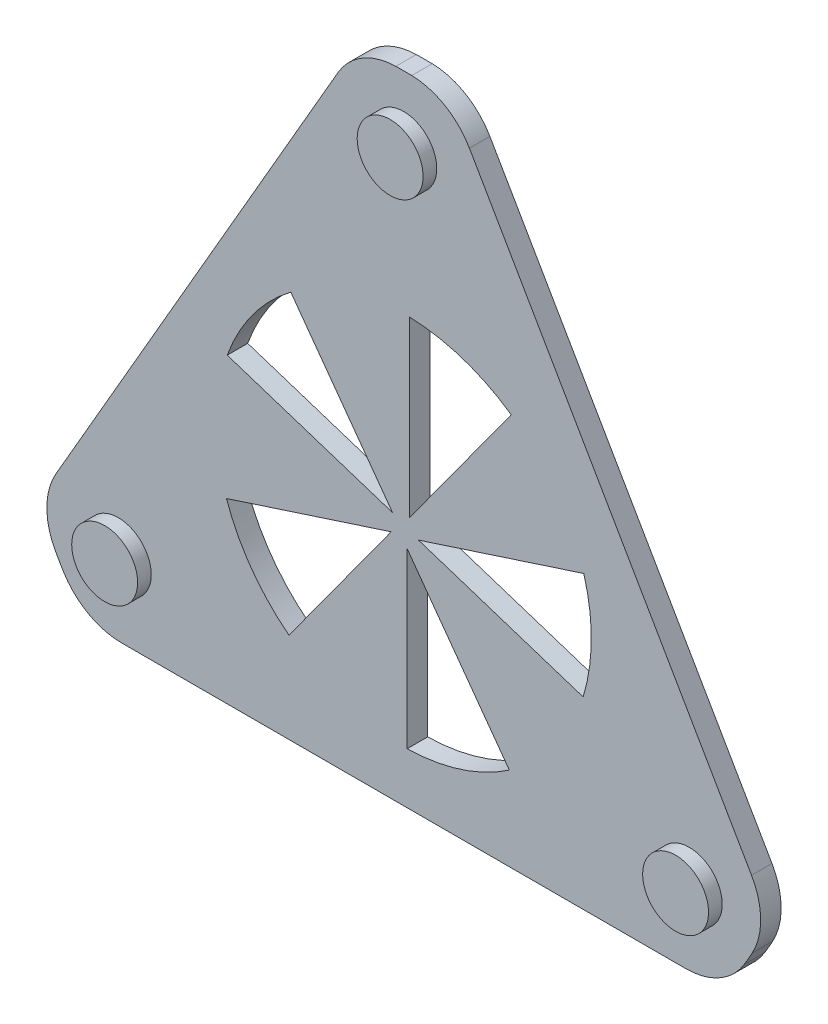
SolidWorks part; units mm, degrees
ref_plane "Спереди" through (0, 0, 0) normal (0, 0, 1) x (1, 0, 0)
ref_plane "Сверху" through (0, 0, 0) normal (0, 1, 0) x (1, 0, 0)
ref_plane "Справа" through (0, 0, 0) normal (1, 0, 0) x (0, 0, -1)
sketch "Sketch1" plane through (0, 0, 0) normal (0, 0, 1) x (1, 0, 0)
  line L0 (3.9, 6.755) -> (7.8, 0) construction
  line L2 (5.85, 10.1325) -> (11.7, 0) construction
  line L4 (7.8, 13.51) -> (15.6, 0) construction
  circle A61 centre (0, 0) radius 20
  circle A131 centre (0, 0) radius 1.25
  circle A484 centre (3.9, 0) radius 1.25
  circle A485 centre (7.8, 0) radius 1.25
  circle A486 centre (11.7, 0) radius 1.25
  circle A487 centre (15.6, 0) radius 1.25
  circle A488 centre (1.95, -3.3775) radius 1.25
  circle A489 centre (3.9, -6.755) radius 1.25
  circle A490 centre (5.85, -10.1325) radius 1.25
  circle A491 centre (7.8, -13.51) radius 1.25
  circle A492 centre (-1.95, -3.3775) radius 1.25
  circle A493 centre (-3.9, -6.755) radius 1.25
  circle A494 centre (-5.85, -10.1325) radius 1.25
  circle A495 centre (-7.8, -13.51) radius 1.25
  circle A496 centre (-3.9, 0) radius 1.25
  circle A497 centre (-7.8, 0) radius 1.25
  circle A498 centre (-11.7, 0) radius 1.25
  circle A499 centre (-15.6, 0) radius 1.25
  circle A500 centre (-1.95, 3.3775) radius 1.25
  circle A501 centre (-3.9, 6.755) radius 1.25
  circle A502 centre (-5.85, 10.1325) radius 1.25
  circle A503 centre (-7.8, 13.51) radius 1.25
  circle A504 centre (1.95, 3.3775) radius 1.25
  circle A505 centre (3.9, 6.755) radius 1.25
  circle A506 centre (5.85, 10.1325) radius 1.25
  circle A507 centre (7.8, 13.51) radius 1.25
  circle A508 centre (5.85, 3.3775) radius 1.25
  circle A509 centre (7.8, 6.755) radius 1.25
  circle A510 centre (9.75, 3.3775) radius 1.25
  circle A511 centre (11.7, 6.755) radius 1.25
  circle A512 centre (9.7491, 10.1341) radius 1.25
  circle A513 centre (13.6509, 3.3759) radius 1.25
  circle A514 centre (5.85, -3.3791) radius 1.25
  circle A515 centre (9.75, -3.3791) radius 1.25
  circle A516 centre (7.8, -6.7566) radius 1.25
  circle A517 centre (11.7, -6.7566) radius 1.25
  circle A518 centre (9.7491, -10.1356) radius 1.25
  circle A519 centre (13.6509, -3.3775) radius 1.25
  circle A520 centre (-0.0013, -6.7573) radius 1.25
  circle A521 centre (1.9487, -10.1348) radius 1.25
  circle A522 centre (-1.9513, -10.1348) radius 1.25
  circle A523 centre (-0.0013, -13.5123) radius 1.25
  circle A524 centre (-3.9032, -13.5123) radius 1.25
  circle A525 centre (3.9005, -13.5123) radius 1.25
  circle A526 centre (-5.8527, -3.3791) radius 1.25
  circle A527 centre (-7.8027, -6.7566) radius 1.25
  circle A528 centre (-9.7527, -3.3791) radius 1.25
  circle A529 centre (-11.7027, -6.7566) radius 1.25
  circle A530 centre (-13.6536, -3.3775) radius 1.25
  circle A531 centre (-9.7518, -10.1356) radius 1.25
  circle A532 centre (-5.8527, 3.3775) radius 1.25
  circle A533 centre (-9.7527, 3.3775) radius 1.25
  circle A534 centre (-7.8027, 6.755) radius 1.25
  circle A535 centre (-11.7027, 6.755) radius 1.25
  circle A536 centre (-9.7518, 10.1341) radius 1.25
  circle A537 centre (-13.6536, 3.3759) radius 1.25
  circle A538 centre (-0.0014, 6.7558) radius 1.25
  circle A539 centre (-1.9514, 10.1333) radius 1.25
  circle A540 centre (1.9486, 10.1333) radius 1.25
  circle A541 centre (-0.0014, 13.5108) radius 1.25
  circle A542 centre (3.9005, 13.5108) radius 1.25
  circle A543 centre (-3.9032, 13.5108) radius 1.25
  circle A544 centre (13.65, -1.1258) radius 2.2517 construction
  circle A545 centre (11.7009, -4.5044) radius 2.2522 construction
  circle A546 centre (9.75, -7.8834) radius 2.2522 construction
  circle A547 centre (7.7987, -11.2591) radius 2.2509 construction
  circle A548 centre (13.65, -1.1258) radius 0.65
  circle A549 centre (11.7009, -4.5044) radius 0.65
  circle A550 centre (9.75, -7.8834) radius 0.65
  circle A551 centre (7.7987, -11.2591) radius 0.65
  circle A552 centre (9.75, -1.1258) radius 0.65
  circle A553 centre (7.8009, -4.5044) radius 0.65
  circle A554 centre (5.85, -7.8834) radius 0.65
  circle A555 centre (3.8987, -11.2591) radius 0.65
  circle A556 centre (5.85, -1.1258) radius 0.65
  circle A557 centre (3.9009, -4.5044) radius 0.65
  circle A558 centre (1.95, -7.8834) radius 0.65
  circle A559 centre (-0.0013, -11.2591) radius 0.65
  circle A560 centre (1.95, -1.1258) radius 0.65
  circle A561 centre (0.0009, -4.5044) radius 0.65
  circle A562 centre (-1.95, -7.8834) radius 0.65
  circle A563 centre (-3.9013, -11.2591) radius 0.65
  circle A564 centre (-1.95, -1.1258) radius 0.65
  circle A565 centre (-3.8991, -4.5044) radius 0.65
  circle A566 centre (-5.85, -7.8834) radius 0.65
  circle A567 centre (-7.8013, -11.2591) radius 0.65
  circle A568 centre (-5.85, -1.1258) radius 0.65
  circle A569 centre (-7.7991, -4.5044) radius 0.65
  circle A570 centre (-9.75, -7.8834) radius 0.65
  circle A572 centre (-9.75, -1.1258) radius 0.65
  circle A573 centre (-11.6991, -4.5044) radius 0.65
  circle A576 centre (-13.65, -1.1258) radius 0.65
  circle A587 centre (0, 2.2517) radius 2.2517 construction
  circle A588 centre (0, 2.2517) radius 0.65
  circle A589 centre (3.9, 2.2517) radius 0.65
  circle A590 centre (7.8, 2.2517) radius 0.65
  circle A591 centre (11.7, 2.2517) radius 0.65
  circle A592 centre (15.6, 2.2517) radius 0.65
  circle A593 centre (1.9491, 5.6297) radius 2.2522 construction
  circle A594 centre (1.9491, 5.6297) radius 0.65
  circle A595 centre (5.8491, 5.6297) radius 0.65
  circle A596 centre (9.7491, 5.6297) radius 0.65
  circle A597 centre (13.6491, 5.6297) radius 0.65
  circle A598 centre (3.8991, 9.0072) radius 2.2522 construction
  circle A599 centre (3.8991, 9.0072) radius 0.65
  circle A600 centre (7.7991, 9.0072) radius 0.65
  circle A601 centre (11.6991, 9.0072) radius 0.65
  circle A602 centre (5.85, 12.3842) radius 2.2517 construction
  circle A603 centre (5.85, 12.3842) radius 0.65
  circle A604 centre (9.75, 12.3842) radius 0.65
  circle A605 centre (5.85, -14.6358) radius 0.65
  circle A606 centre (1.9509, -14.6353) radius 0.65
  circle A607 centre (-1.9491, -14.6353) radius 0.65
  circle A608 centre (-5.85, -14.6358) radius 0.65
  circle A609 centre (-15.6, 2.2517) radius 0.65
  circle A610 centre (-13.65, 5.6281) radius 0.65
  circle A611 centre (-11.7, 9.0056) radius 0.65
  circle A612 centre (-9.75, 12.3842) radius 0.65
  circle A613 centre (-5.85, 12.3842) radius 0.65
  circle A614 centre (-1.95, 12.3842) radius 0.65
  circle A615 centre (1.95, 12.3842) radius 0.65
  circle A616 centre (-7.8, 9.0056) radius 0.65
  circle A617 centre (-9.75, 5.6281) radius 0.65
  circle A618 centre (-11.7, 2.2517) radius 0.65
  circle A619 centre (-3.9, 9.0056) radius 0.65
  circle A620 centre (-5.85, 5.6281) radius 0.65
  circle A621 centre (-7.8, 2.2517) radius 0.65
  circle A622 centre (0, 9.0056) radius 0.65
  circle A623 centre (-1.95, 5.6281) radius 0.65
  circle A624 centre (-3.9, 2.2517) radius 0.65
  circle A625 centre (-15.5991, -4.5044) radius 0.65
  circle A626 centre (-13.65, -7.8834) radius 0.65
  circle A627 centre (-17.55, -7.8834) radius 0.65
  circle A628 centre (-19.5013, -11.2591) radius 0.65
  circle A629 centre (-15.6013, -11.2591) radius 0.65
  circle A630 centre (-11.7013, -11.2591) radius 0.65
  point P51 (0, 0)
  point P125 (-0.0013, -0.0008)
  point P231 (0, 0)
  dimension "D1" = 5
  dimension "D3" = 6
  dimension "D5" = 8
  dimension "D7" = 4
  dimension "D11" = 4
  dimension "D2" = 6
  dimension "D6" = 5
  dimension "D8" = 3
  dimension "D9" = 2
  dimension "D4" = 1.3
  dimension "D10" = 3
ref_plane "Plane1" through (0, 0, 10) normal (0, 0, 1) x (1, 0, 0)
sketch "Sketch2" plane through (0, 0, 10) normal (0, 0, 1) x (1, 0, 0)
  line L0 (0, 0.2409) -> (0, 17)
  line L62 (0.1416, 0.1949) -> (9.9923, 13.7533)
  line L71 (0.2291, 0.0744) -> (16.168, 5.2533)
  line L92 (0.2291, -0.0744) -> (16.168, -5.2533)
  line L101 (0.1416, -0.1949) -> (9.9923, -13.7533)
  line L110 (0, -0.2409) -> (0, -17)
  line L119 (-0.1416, -0.1949) -> (-9.9923, -13.7533)
  line L124 (-0.2291, -0.0744) -> (-16.168, -5.2533)
  line L133 (-0.2291, 0.0744) -> (-16.168, 5.2533)
  line L142 (-0.1416, 0.1949) -> (-9.9923, 13.7533)
  line L183 (0.5, -0.2001) -> (0.5, 16.4924)
  line L185 (9.4541, 13.5229) -> (0.0202, 0.5382)
  line L186 (15.7825, -4.8126) -> (0.5181, 0.1471)
  line L187 (-0.0358, -0.5374) -> (15.8397, 4.6209)
  line L188 (0.3, -16.4973) -> (0.3, -0.4473)
  line L189 (-0.5221, -0.132) -> (9.2895, -13.6365)
  line L190 (-15.5971, -5.3833) -> (-0.3327, -0.4235)
  line L191 (-0.2869, 0.4558) -> (-10.0985, -13.0488)
  line L192 (-9.9396, 13.1702) -> (-0.5056, 0.1855)
  line L193 (0.3448, 0.4137) -> (-15.5307, 5.572)
  circle A52 centre (0, 0) radius 17
  circle A53 centre (0, 0) radius 18
  circle A199 centre (0, 0) radius 0.2409
  circle A246 centre (0, 0) radius 0.5386
  circle A247 centre (0, 0) radius 16.5
  point P39 (0, 0)
  point P80 (0, 0)
  point P108 (0, 0)
  dimension "D1" = 10
  dimension "D4" = 5
  dimension "D2" = 0.5
  dimension "D5" = 1
  dimension "D6" = 36
  dimension "D7" = 0.5
  dimension "D3" = 0.3
extrude "Boss-Extrude1" add sketch "Sketch2" against normal blind 1.8 contours A53 A52 | L187 A247 L71 A199 | L62 A247 L185 A199 | L183 A247 L0 A199 | L142 A247 L192 A199 | L193 A247 L133 A199 | L124 A247 L190 A199 | L191 A247 L119 A199 | L110 A247 L188 A199 | L189 A247 L101 A199 | L92 A247 L186 A199 | A247 L62 A52 L0 | A247 L142 A52 L133 | A247 L124 A52 L119 | A247 L110 A52 L101 | A247 L92 A52 L71 | A246 L62 L183 L185 L0 | A246 L92 L187 L186 L71 | A246 L110 L189 L188 L101 | A246 L124 L191 L190 L119 | A246 L142 L193 L192 L133
sketch "Sketch11" plane through (0, 0, 8.2) normal (0, 0, -1) x (-1, 0, 0)
  line L0 (0, 0.5386) -> (0, 18)
  line L1 (0.3166, 0.4357) -> (10.702, 14.4729)
  line L2 (0.5122, -0.1664) -> (17.0717, -5.7059)
  line L3 (0.5122, 0.1664) -> (17.119, 5.5623)
  line L4 (0, -0.5386) -> (-0.1512, -17.9994)
  line L5 (0.3166, -0.4357) -> (10.5801, -14.5623)
  line L6 (-0.5122, -0.1664) -> (-17.1651, -5.4184)
  line L7 (-0.3166, -0.4357) -> (-10.5801, -14.5623)
  line L8 (-0.3166, 0.4357) -> (-10.4575, 14.6506)
  line L9 (-0.5122, 0.1664) -> (-17.119, 5.5623)
  circle A0 centre (0, 0) radius 0.5386
  arc A1 (0, 0.5386) -> (-0.3166, 0.4357) centre (0, 0) ccw construction
  arc A2 (-0.5122, 0.1664) -> (-0.5122, -0.1664) centre (0, 0) ccw construction
  circle A5 centre (0, 0) radius 18 construction
  arc A6 (0, 18) -> (10.702, 14.4729) centre (0, 0) cw
  arc A8 (17.119, 5.5623) -> (17.0717, -5.7059) centre (0, 0) cw
  arc A10 (10.5801, -14.5623) -> (-0.1512, -17.9994) centre (0, 0) cw
  arc A12 (-10.5801, -14.5623) -> (-17.1651, -5.4184) centre (0, 0) cw
  arc A14 (-17.119, 5.5623) -> (-10.4575, 14.6506) centre (0, 0) cw
  point P63 (0, 0)
  dimension "D1" = 5
extrude "Boss-Extrude7" add sketch "Sketch11" against normal blind 1.8
sketch "Sketch13" plane through (0, 0, 8.2) normal (0, 0, -1) x (-1, 0, 0)
  circle A0 centre (0, 0) radius 3.3
extrude "Boss-Extrude8" [suppressed] add sketch "Sketch13" against normal blind 3
sketch "Sketch14" plane through (0, 0, 10) normal (0, 0, 1) x (1, 0, 0)
  circle A0 centre (0, 0) radius 17
  circle A1 centre (0, 0) radius 17 construction
sketch "Sketch9" plane through (0, 0, 10) normal (0, 0, 1) x (1, 0, 0)
  circle A0 centre (0, 0) radius 3.0981
sketch "Sketch16" plane through (0, 0, 10) normal (0, 0, 1) x (1, 0, 0)
  circle A0 centre (0, 0) radius 3.3
sketch "Sketch17" plane through (0, 0, 8.2) normal (0, 0, -1) x (-1, 0, 0)
  circle A0 centre (0, 0) radius 0.7
extrude "Boss-Extrude9" add sketch "Sketch17" against normal up to surface (1.8 mm away) up to face at (3.3661, -10.6845, 10)
extrude "Boss-Extrude5" [suppressed] add sketch "Sketch9" against normal up to surface (10 mm away)
sketch "Sketch3" plane through (0, 0, 8.2) normal (0, 0, -1) x (-1, 0, 0)
  circle A0 centre (0, 0) radius 17.6
  circle A1 centre (0, 0) radius 35
  circle M33 centre (0, 0) radius 18
extrude "Boss-Extrude2" add sketch "Sketch3" against normal blind 1.8 contours A1 M33
sketch "Sketch4" plane through (0, 0, 8.2) normal (0, 0, -1) x (-1, 0, 0)
  circle A0 centre (0, 0) radius 29 construction
  circle A1 centre (0, 29) radius 2.9
  circle A2 centre (25.1147, -14.5) radius 2.9
  circle A3 centre (-25.1147, -14.5) radius 2.9
  point P11 (0, 0)
  dimension "D1" = 3
extrude "Boss-Extrude3" add sketch "Sketch4" against normal blind 3
sketch "Sketch6" plane through (0, 0, 10) normal (0, 0, -1) x (-1, 0, 0)
  circle A0 centre (0, 30) radius 5
  circle A2 centre (25.9808, -15) radius 5
  circle A3 centre (-25.9808, -15) radius 5
  point P10 (0, 0)
  dimension "D1" = 3
extrude "Boss-Extrude4" add sketch "Sketch6" along normal blind 1
sketch "Sketch7" plane through (0, 0, 8.2) normal (0, 0, -1) x (-1, 0, 0)
  line L1 (0, 42) -> (-36.3731, -21)
  line L2 (-36.3731, -21) -> (36.3731, -21)
  line L3 (36.3731, -21) -> (0, 42)
  circle A2 centre (0, 0) radius 21 construction
  circle A3 centre (0, 0) radius 59.1314
extrude "Cut-Extrude1" cut sketch "Sketch7" against normal blind 10
fillet "Fillet1" radius 6 6 edges at (-32.1865, -13.7487, 9.1) (-4.1865, 34.7487, 9.1) (28, -21, 9.1) (-28, -21, 9.1) (4.1865, 34.7487, 9.1) (32.1865, -13.7487, 9.1)
